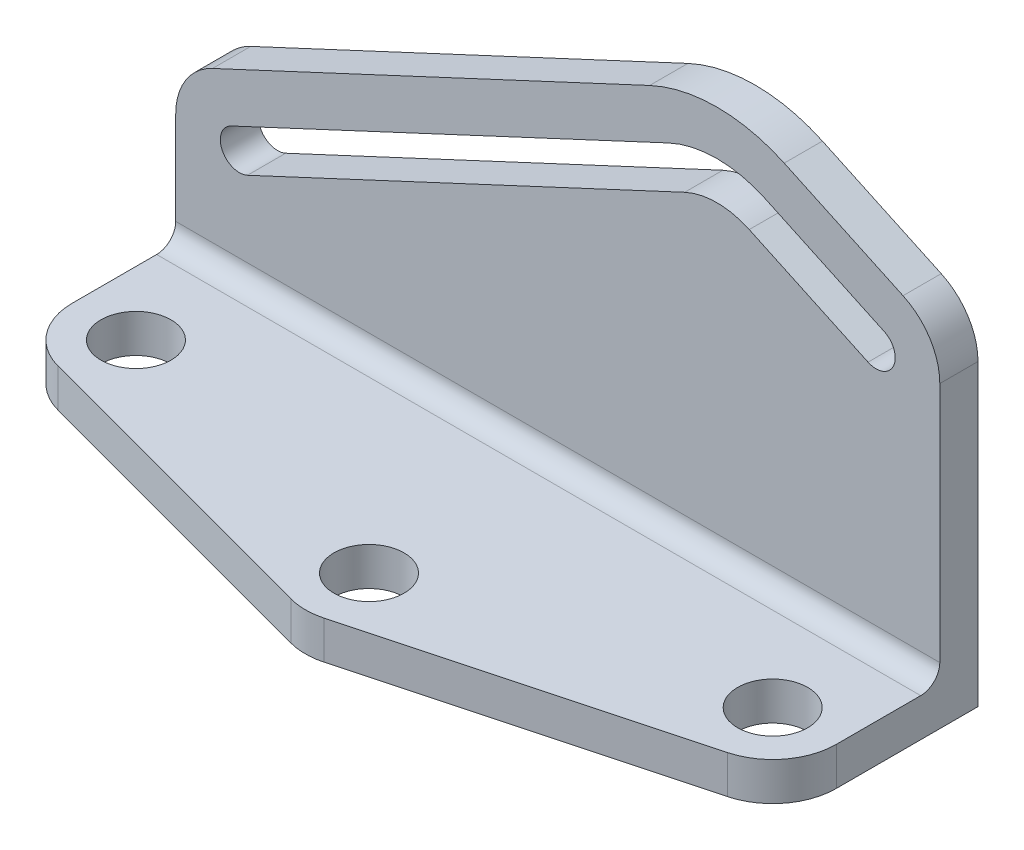
SolidWorks part; units mm, degrees
material "Промышленная бронза, UNS C22000 (90-10 Бронза)"
ref_plane "Спереди" through (0, 0, 0) normal (0, 0, 1) x (1, 0, 0)
ref_plane "Сверху" through (0, 0, 0) normal (0, 1, 0) x (1, 0, 0)
ref_plane "Справа" through (0, 0, 0) normal (1, 0, 0) x (0, 0, -1)
sketch "Эскиз1" plane through (0, 0, 0) normal (0, 0, 1) x (1, 0, 0)
  line L0 (-60, 0) -> (-60, 23.6293)
  line L1 (-54.2262, 32.6924) -> (14.4345, 64.7094)
  line L2 (35.5655, 64.7094) -> (54.2262, 56.0078)
  line L3 (60, 46.9447) -> (60, 0)
  line L4 (60, 0) -> (-60, 0)
  arc A0 (54.2262, 56.0078) -> (60, 46.9447) centre (50, 46.9447) cw
  arc A1 (14.4345, 64.7094) -> (35.5655, 64.7094) centre (25, 42.0517) cw
  arc A2 (-60, 23.6293) -> (-54.2262, 32.6924) centre (-50, 23.6293) cw
  point P10 (25, 69.6362)
  point P13 (-60, 30)
  dimension "D6" = 10
  dimension "D7" = 25
  dimension "D1" = 120
  dimension "D2" = 65
  dimension "D3" = 130
  dimension "D4" = 30
  dimension "D5" = 85
extrude "Бобышка-Вытянуть1" add sketch "Эскиз1" along normal blind 6
sketch "Эскиз2" plane through (0, 0, 0) normal (0, -1, 0) x (1, 0, 0)
  line L0 (-60, 6) -> (60, 6) construction
  line L1 (-60, 6) -> (60, 6)
  line L2 (-60, 6) -> (-60, 22.2498)
  line L3 (-52.5882, 31.909) -> (-2.5882, 45.3065)
  line L4 (2.5882, 45.3065) -> (52.5882, 31.909)
  line L5 (60, 22.2498) -> (60, 6)
  arc A0 (52.5882, 31.909) -> (60, 22.2498) centre (50, 22.2498) cw
  arc A1 (-2.5882, 45.3065) -> (2.5882, 45.3065) centre (0, 35.6472) cw
  arc A2 (-60, 22.2498) -> (-52.5882, 31.909) centre (-50, 22.2498) cw
  circle A3 centre (-50, 22.2498) radius 5.5
  circle A4 centre (0, 35.6472) radius 5.5
  circle A5 centre (50, 22.2498) radius 5.5
  point P10 (0, 46)
  dimension "D3" = 10
  dimension "D4" = 11
  dimension "D1" = 40
  dimension "D2" = 150
extrude "Бобышка-Вытянуть2" add sketch "Эскиз2" against normal blind 6
fillet "Скругление1" radius 3 1 edges at (0, 6, 6)
sketch "Эскиз3" plane through (0, 0, 6) normal (0, 0, 1) x (1, 0, 0)
  line L2 (51.2679, 49.6636) -> (32.6071, 58.3652)
  line L3 (17.3929, 58.3652) -> (-51.2679, 26.3482)
  line L4 (50, 46.9447) -> (31.3393, 55.6463)
  line L5 (18.6607, 55.6463) -> (-50, 23.6293)
  line L6 (50, 46.9447) -> (31.3393, 55.6463) construction
  line L7 (18.6607, 55.6463) -> (-50, 23.6293) construction
  line L8 (48.7321, 44.2258) -> (30.0714, 52.9274)
  line L9 (19.9286, 52.9274) -> (-48.7321, 20.9104)
  arc A1 (32.6071, 58.3652) -> (17.3929, 58.3652) centre (25, 42.0517) ccw
  arc A2 (31.3393, 55.6463) -> (18.6607, 55.6463) centre (25, 42.0517) ccw
  arc A3 (31.3393, 55.6463) -> (18.6607, 55.6463) centre (25, 42.0517) ccw construction
  arc A4 (30.0714, 52.9274) -> (19.9286, 52.9274) centre (25, 42.0517) ccw
  arc A5 (51.2679, 49.6636) -> (48.7321, 44.2258) centre (50, 46.9447) cw
  arc A6 (-51.2679, 26.3482) -> (-48.7321, 20.9104) centre (-50, 23.6293) ccw
  dimension "D1" = 10
  dimension "D2" = 3
  dimension "D3" = 3
extrude "Вырез-Вытянуть1" cut sketch "Эскиз3" against normal through all
